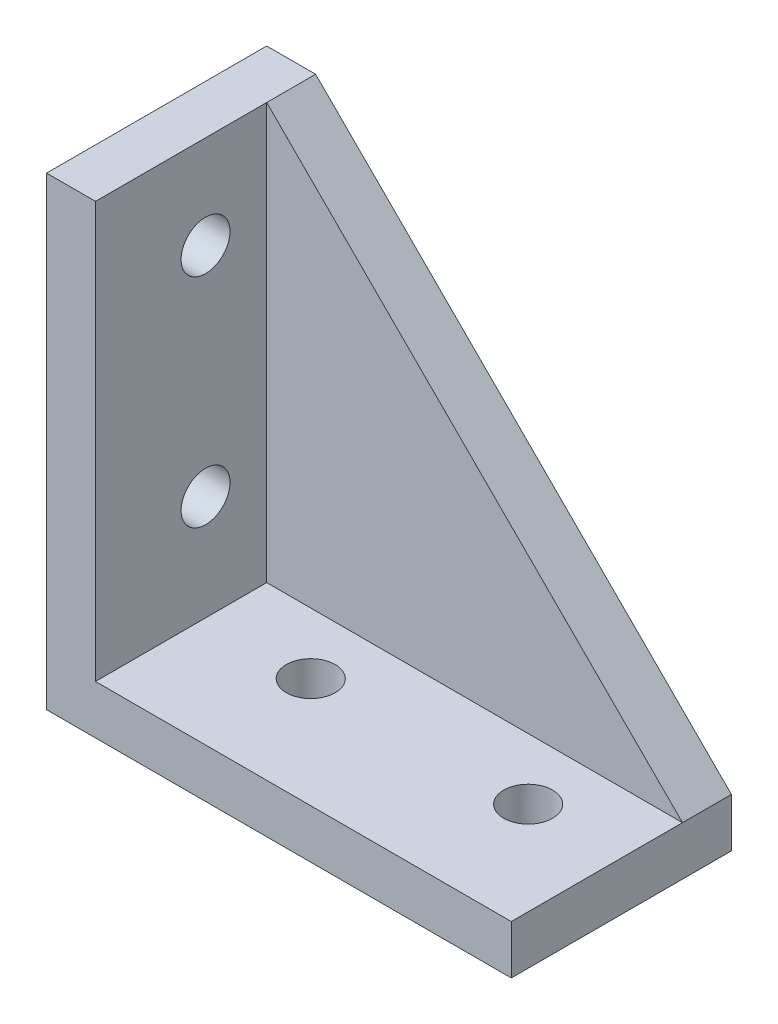
SolidWorks part; units mm, degrees
ref_plane "Front Plane" through (0, 0, 0) normal (0, 0, 1) x (1, 0, 0)
ref_plane "Top Plane" through (0, 0, 0) normal (0, 1, 0) x (1, 0, 0)
ref_plane "Right Plane" through (0, 0, 0) normal (1, 0, 0) x (0, 0, -1)
sketch "Sketch1" plane through (0, 0, 0) normal (0, 0, 1) x (1, 0, 0)
  line L0 (0, 0) -> (0, 38)
  line L2 (38, 0) -> (0, 0)
  line L3 (0, 38) -> (4, 38)
  line L4 (4, 38) -> (4, 4)
  line L5 (4, 4) -> (38, 4)
  line L6 (38, 4) -> (38, 0)
  point P4 (8.3665, 8.3665)
  dimension "D1" = 38
  dimension "D2" = 38
  dimension "D3" = 4
extrude "Boss-Extrude1" add sketch "Sketch1" along normal blind 14
sketch "Sketch2" plane through (0, 0, 0) normal (0, 0, -1) x (-1, 0, 0)
  line L0 (-4, 38) -> (-38, 4)
  line L7 (-38, 0) -> (0, 0)
  line L8 (0, 0) -> (0, 38)
  line L9 (0, 38) -> (-4, 38)
  line L10 (-4, 38) -> (-4, 4)
  line L11 (-4, 4) -> (-38, 4)
  line L12 (-38, 4) -> (-38, 0)
  line L13 (-38, 0) -> (0, 0)
  line L14 (0, 0) -> (0, 38)
  line L15 (0, 38) -> (-4, 38)
  line L16 (-4, 38) -> (-4, 4)
  line L17 (-4, 4) -> (-38, 4)
  line L18 (-38, 4) -> (-38, 0)
  point P0 (-4, 38)
  point P1 (0, 0)
  point P6 (-37.65, 4)
  point P8 (-38, 4)
  point P12 (-38, 4)
  line M1 (-38, 0) -> (0, 0)
  line M2 (0, 0) -> (0, 38)
  line M3 (0, 38) -> (-4, 38)
  line M4 (-4, 38) -> (-4, 4)
  line M5 (-4, 4) -> (-38, 4)
  line M6 (-38, 4) -> (-38, 0)
  dimension "D1" = 0
extrude "Boss-Extrude2" add sketch "Sketch2" along normal blind 4 contours L0 M4 M5 | M6 M1 M2 M3 M4 M5
sketch "Sketch3" plane through (4, 0, 0) normal (1, 0, 0) x (0, 0, -1)
  line L0 (-14, 38) -> (4, 38) construction
  line L1 (4, 38) -> (4, 4) construction
  line L2 (-5, 38) -> (-5, 0) construction
  line L3 (-14, 0) -> (4, 0) construction
  circle A0 centre (-5, 30.38) radius 2
  circle A1 centre (-5, 12.6) radius 2
  point P13 (0, 0)
  dimension "D1" = 4
  dimension "D2" = 7.62
  dimension "D3" = 17.78
extrude "Cut-Extrude1" cut sketch "Sketch3" against normal up to surface (4 mm away) contours A0 | A1 up to face at (0, 19, 5)
ref_plane "Plane2" through (0, 0, 0) normal (0.7071, -0.7071, 0) x (0, 0, -1)
mirror "Mirror4" about plane through (0, 0, 0) normal (0.7071, -0.7071, 0) of "Cut-Extrude1"
